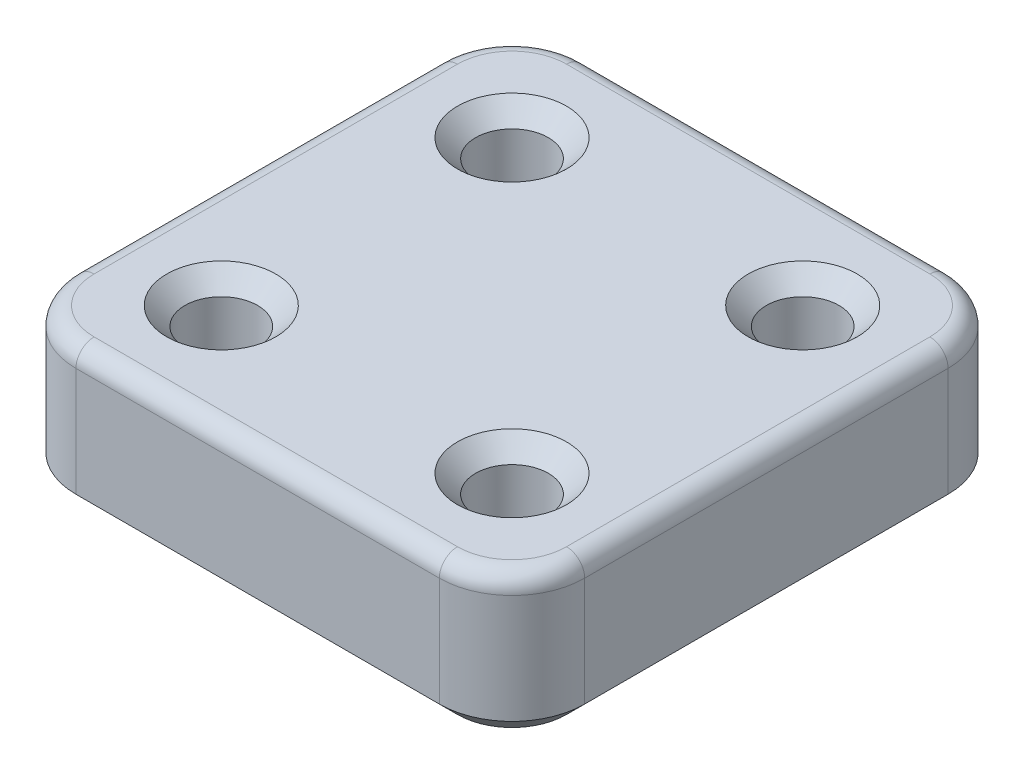
SolidWorks part; units mm, degrees
ref_plane "Front Plane" through (0, 0, 0) normal (0, 0, 1) x (1, 0, 0)
ref_plane "Top Plane" through (0, 0, 0) normal (0, 1, 0) x (1, 0, 0)
ref_plane "Right Plane" through (0, 0, 0) normal (1, 0, 0) x (0, 0, -1)
sketch "Sketch2" plane through (0, 0, 0) normal (0, 1, 0) x (1, 0, 0)
  line L0 (-12.7, 12.7) -> (12.7, -12.7) construction
  line L1 (-12.7, 12.7) -> (12.7, 12.7) construction
  line L2 (-12.7, 12.7) -> (-12.7, -12.7) construction
  line L3 (-12.7, -12.7) -> (12.7, -12.7) construction
  line L4 (12.7, 12.7) -> (12.7, -12.7) construction
  line L5 (12.7, 12.7) -> (-12.7, -12.7) construction
  line L7 (-22.225, -22.225) -> (22.225, -22.225)
  line L8 (-22.225, -22.225) -> (-22.225, 22.225)
  line L9 (-22.225, 22.225) -> (22.225, 22.225)
  line L10 (22.225, -22.225) -> (22.225, 22.225)
  line L11 (-22.225, -22.225) -> (22.225, 22.225) construction
  line L12 (-22.225, 22.225) -> (22.225, -22.225) construction
  circle A3 centre (-12.7, -12.7) radius 3.175
  circle A4 centre (12.7, -12.7) radius 3.175
  circle A5 centre (12.7, 12.7) radius 3.175
  circle A6 centre (-12.7, 12.7) radius 3.175
  point P5 (0, 0)
  dimension "D2" = 6.35
  dimension "D1" = 25.4
  dimension "D3" = 9.525
  dimension "D4" = 9.525
extrude "Boss-Extrude1" add sketch "Sketch2" along normal blind 12.7
fillet "Fillet1" radius 6.35 4 edges at (22.225, 6.35, 22.225) (-22.225, 6.35, -22.225) (22.225, 6.35, -22.225) (-22.225, 6.35, 22.225)
fillet "Fillet2" radius 1.5875 8 edges at (-20.3651, 12.7, -20.3651) (0, 12.7, -22.225) (20.3651, 12.7, -20.3651) (22.225, 12.7, 0) (20.3651, 12.7, 20.3651) (0, 12.7, 22.225) (-20.3651, 12.7, 20.3651) (-22.225, 12.7, 0)
chamfer "Chamfer1" distance 1.5875 angle 45 16 edges at (-12.7, 0, -9.525) (12.7, 0, 15.875) (20.3651, 0, -20.3651) (0, 0, -22.225) (-20.3651, 0, -20.3651) (-22.225, 0, 0) (-20.3651, 0, 20.3651) (0, 0, 22.225) (20.3651, 0, 20.3651) (22.225, 0, 0) (-12.7, 0, 15.875) (12.7, 0, -9.525) (-12.7, 12.7, -9.525) (12.7, 12.7, -9.525) (12.7, 12.7, 15.875) (-12.7, 12.7, 15.875)
equation "\"D3@Sketch2\"=\"D2@Sketch2\"/2+0.25"
equation "\"D4@Sketch2\"=\"D3@Sketch2\""
